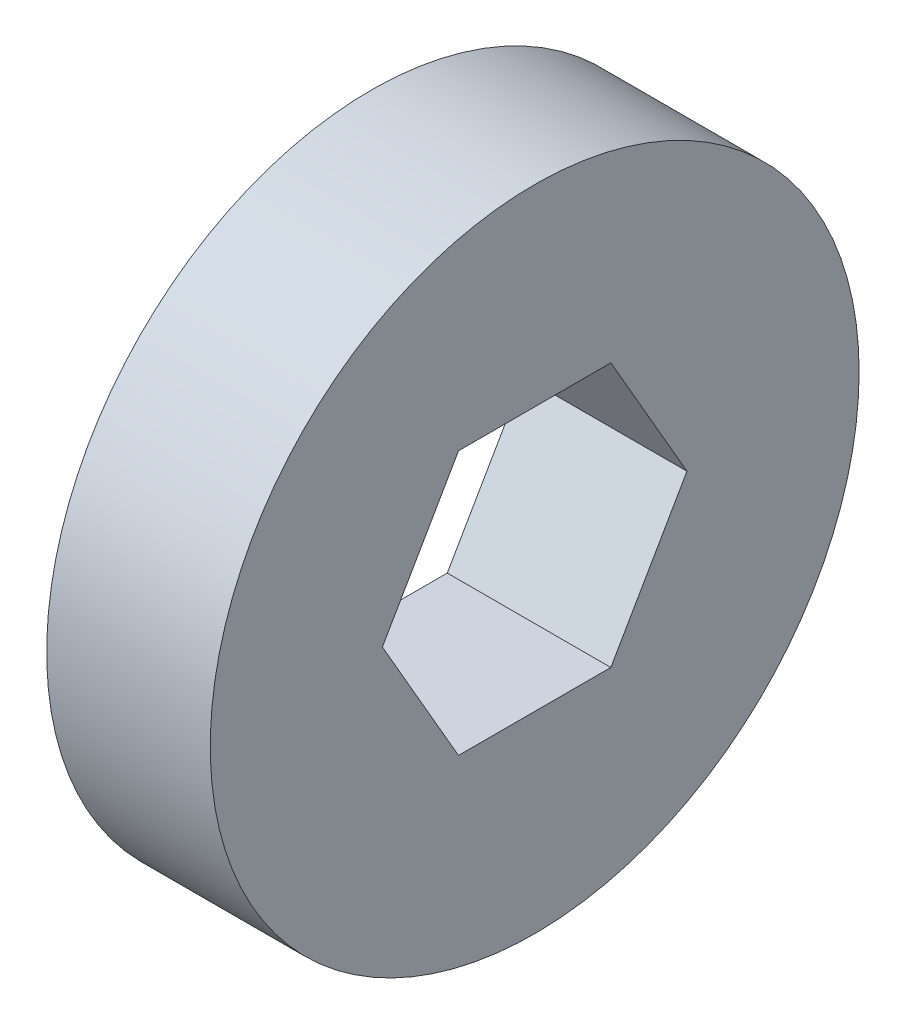
SolidWorks part; units mm, degrees
ref_plane "Front Plane" through (0, 0, 0) normal (0, 0, 1) x (1, 0, 0)
ref_plane "Top Plane" through (0, 0, 0) normal (0, 1, 0) x (1, 0, 0)
ref_plane "Right Plane" through (0, 0, 0) normal (1, 0, 0) x (0, 0, -1)
sketch "Sketch1" plane through (0, 0, 0) normal (1, 0, 0) x (0, 0, -1)
  line L1 (3.6662, 6.35) -> (-3.6662, 6.35)
  line L2 (-3.6662, 6.35) -> (-7.3323, 0)
  line L3 (-7.3323, 0) -> (-3.6662, -6.35)
  line L4 (-3.6662, -6.35) -> (3.6662, -6.35)
  line L5 (3.6662, -6.35) -> (7.3323, 0)
  line L6 (7.3323, 0) -> (3.6662, 6.35)
  circle A0 centre (0, 0) radius 15.621
  circle A1 centre (0, 0) radius 6.35 construction
  circle A2 centre (0, 0) radius 6.858 construction
  dimension "D2" = 31.242
  dimension "D3" = 13.716
  dimension "D1" = 12.7
extrude "Boss-Extrude1" add sketch "Sketch1" along normal blind 7.874
